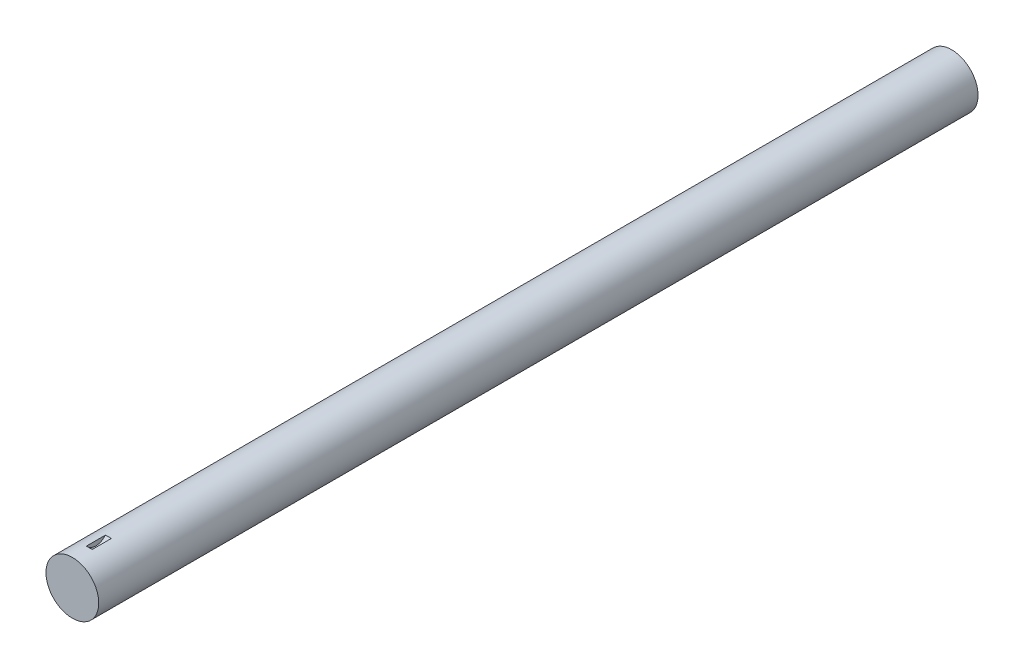
SolidWorks part; units mm, degrees
ref_plane "Front Plane" through (0, 0, 0) normal (0, 0, 1) x (1, 0, 0)
ref_plane "Top Plane" through (0, 0, 0) normal (0, 1, 0) x (1, 0, 0)
ref_plane "Right Plane" through (0, 0, 0) normal (1, 0, 0) x (0, 0, -1)
sketch "Sketch1" plane through (0, 0, 0) normal (0, 0, 1) x (1, 0, 0)
  circle A0 centre (0, 0) radius 9
extrude "Boss-Extrude1" add sketch "Sketch1" along normal mid plane 100
sketch "Sketch2" plane through (0, 0, 0) normal (1, 0, 0) x (0, 0, -1)
  line L2 (-45, 10.5) -> (-37, 10.5)
  line L4 (50, 9) -> (-50, 9) construction
  arc A0 (-45, 10.5) -> (-37, 10.5) centre (-41, 11.5) ccw
  dimension "D4" = 1.5
extrude "Cut-Extrude1" cut sketch "Sketch2" against normal mid plane 2
sketch "Sketch3" plane through (0, 0, -50) normal (0, 0, -1) x (-1, 0, 0)
  circle A0 centre (0, 0) radius 9
extrude "Boss-Extrude2" add sketch "Sketch3" along normal blind 200
